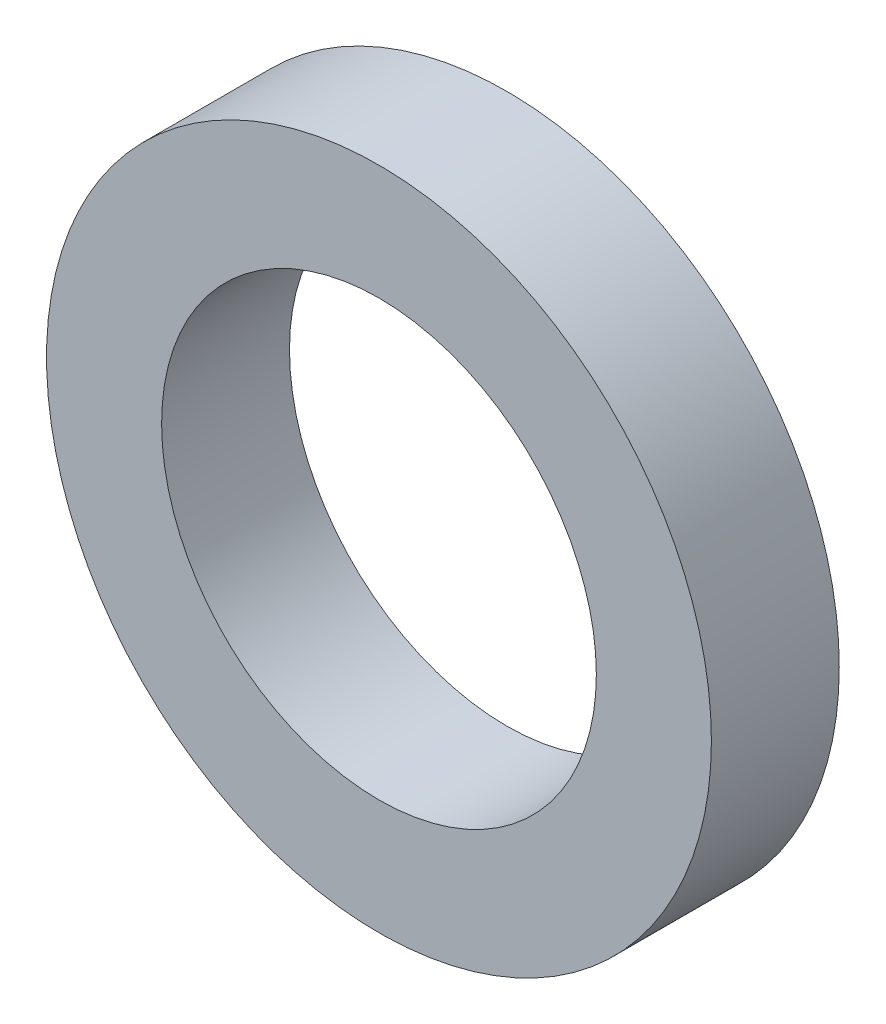
SolidWorks part; units mm, degrees
ref_plane "Спереди" through (0, 0, 0) normal (0, 0, 1) x (1, 0, 0)
ref_plane "Сверху" through (0, 0, 0) normal (0, 1, 0) x (1, 0, 0)
ref_plane "Справа" through (0, 0, 0) normal (1, 0, 0) x (0, 0, -1)
sketch "Эскиз1" plane through (0, 0, 0) normal (0, 0, 1) x (1, 0, 0)
  circle A0 centre (0, 0) radius 13
  circle A1 centre (0, 0) radius 8.5
extrude "Bearing6803" add sketch "Эскиз1" along normal blind 5 from offset 15
